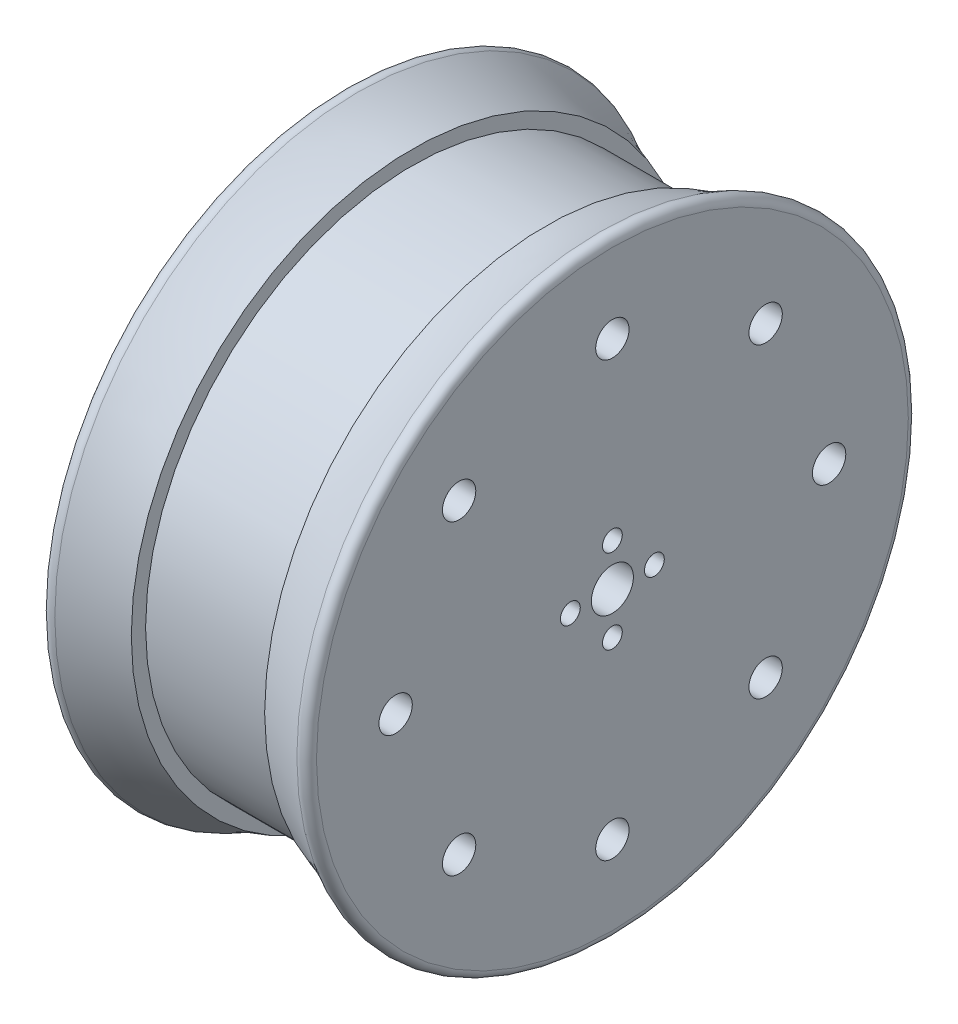
SolidWorks part; units mm, degrees
ref_plane "Front Plane" through (0, 0, 0) normal (0, 0, 1) x (1, 0, 0)
ref_plane "Top Plane" through (0, 0, 0) normal (0, 1, 0) x (1, 0, 0)
ref_plane "Right Plane" through (0, 0, 0) normal (1, 0, 0) x (0, 0, -1)
sketch "Wheel Arc" plane through (0, 0, 0) normal (0, 0, 1) x (1, 0, 0)
  line L0 (0, 0) -> (0, -99.425) construction
  line L1 (-25.4, 0) -> (25.4, 0)
  line L2 (-40.9053, 0) -> (38.2322, 0) construction
  line L3 (-25.4, 0) -> (-25.4, -59.1388)
  line L4 (25.4, 0) -> (25.4, -59.1388)
  line L5 (0, -51.8) -> (0, -50.8) construction
  line L6 (-12.7, -50.8) -> (12.7, -50.8)
  line L7 (-12.7, -50.8) -> (-12.7, -53.5246)
  line L8 (12.7, -50.8) -> (12.7, -53.5246)
  arc A0 (-25.4, -59.1388) -> (-12.7, -53.5246) centre (0, -99.425) cw
  arc A1 (12.7, -53.5246) -> (25.4, -59.1388) centre (0, -99.425) cw
  point P7 (0, 0)
  point P9 (0, 0)
  point P16 (0, -50.8)
  dimension "D6" = 47.625
  dimension "D2" = 50.8
  dimension "D4" = 1
  dimension "D5" = 25.4
  dimension "D1" = 47.625
  dimension "D3" = 51.8
ref_axis "Wheel Axis" through (-40.9053, 0, 0) along (1, 0, 0)
revolve "Wheel" add sketch "Wheel Arc" angle 360 about axis through (-40.9053, 0, 0) along (1, 0, 0)
sketch "Flower" plane through (25.4, 0, 0) normal (1, 0, 0) x (0, 0, -1)
  line L0 (0, 0) -> (0, 8) construction
  circle A0 centre (0, 0) radius 4
  circle A1 centre (0, 8) radius 1.885
  circle A2 centre (8, 0) radius 1.885
  circle A3 centre (0, -8) radius 1.885
  circle A4 centre (-8, 0) radius 1.885
  point P14 (0, 0)
  dimension "D1" = 4
extrude "Mounting" cut sketch "Flower" against normal through all
fillet "Fillet1" radius 1.5875 2 edges at (25.4, 0, 59.1388) (-25.4, 0, 59.1388)
sketch "Sketch1" plane through (25.4, 0, 0) normal (1, 0, 0) x (0, 0, -1)
  line L0 (0, 0) -> (0, 41.275) construction
  circle A0 centre (0, 41.275) radius 3.175
  circle A1 centre (29.1858, 29.1858) radius 3.175
  circle A2 centre (41.275, 0) radius 3.175
  circle A3 centre (29.1858, -29.1858) radius 3.175
  circle A4 centre (0, -41.275) radius 3.175
  circle A5 centre (-29.1858, -29.1858) radius 3.175
  circle A6 centre (-41.275, 0) radius 3.175
  circle A7 centre (-29.1858, 29.1858) radius 3.175
  point P21 (0, 0)
  dimension "D2" = 6.35
  dimension "D1" = 41.275
  dimension "D3" = 8
extrude "Mass_and_Balance" cut sketch "Sketch1" against normal through all
equation "\"BALL_DIAMETER\"= 3.75in"
equation "\"BALL_RADIUS\"= \"BALL_DIAMETER\" / 2"
equation "\"D1@Wheel Arc\"=\"BALL_RADIUS\""
equation "\"D6@Wheel Arc\"=\"BALL_RADIUS\""
